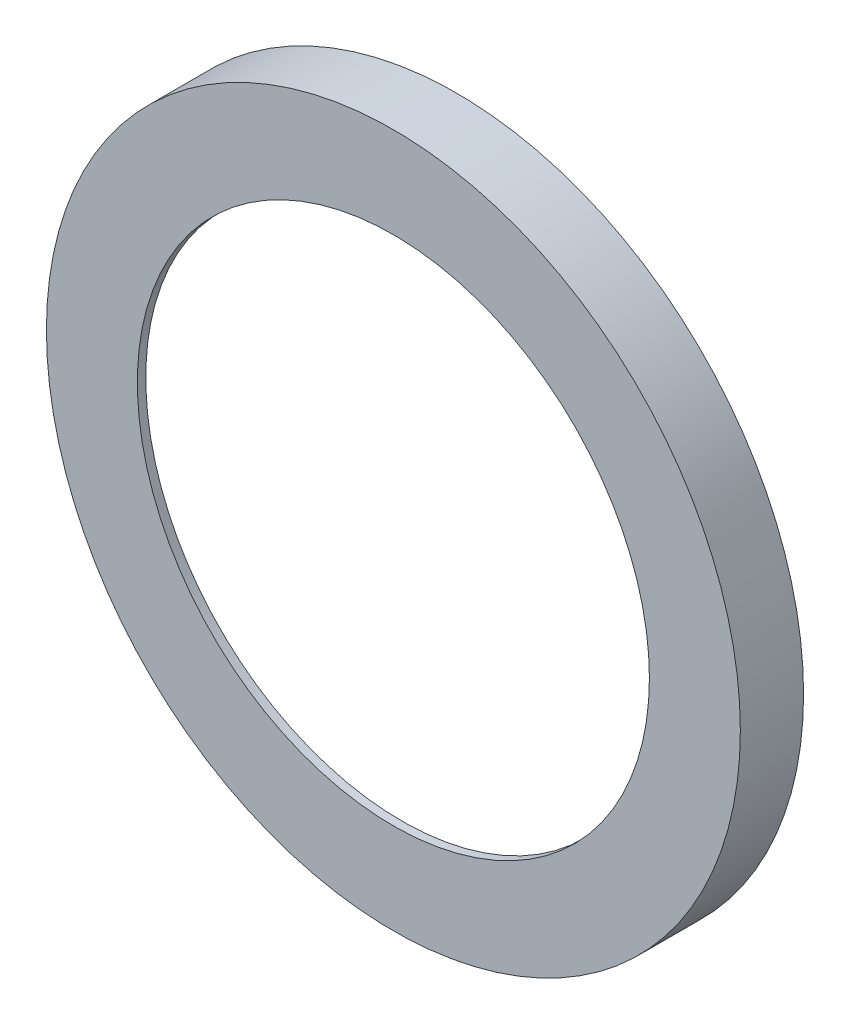
SolidWorks part; units mm, degrees
ref_plane "Front Plane" through (0, 0, 0) normal (0, 0, 1) x (1, 0, 0)
ref_plane "Top Plane" through (0, 0, 0) normal (0, 1, 0) x (1, 0, 0)
ref_plane "Right Plane" through (0, 0, 0) normal (1, 0, 0) x (0, 0, -1)
sketch "Sketch1" plane through (0, 0, 0) normal (0, 1, 0) x (1, 0, 0)
  line L0 (0, 0) -> (0, 55.9741) construction
  line L1 (-171.45, 14.7142) -> (171.45, 14.7142) construction
  line L2 (77.1221, 2.5222) -> (77.1221, 5.0622)
  line L3 (77.1221, 5.0622) -> (100.7008, 21.5722)
  line L4 (100.7008, 21.5722) -> (104.5108, 21.5722)
  line L5 (104.5108, 21.5722) -> (104.5108, 2.5222)
  line L6 (104.5108, 2.5222) -> (77.1221, 2.5222)
  line L8 (76.3601, 1.3792) -> (76.3601, -10.8375) construction
  dimension "D1" = 19.05
  dimension "D2" = 0.762
  dimension "D3" = 3.81
  dimension "D4" = 2.54
  dimension "D5" = 35
  dimension "D6" = 6.858
revolve "Revolve1" add sketch "Sketch1" angle 360 about L0
sketch "Sketch2" [suppressed] plane through (0, 0, -21.5722) normal (0, 0, -1) x (-1, 0, 0)
  line L0 (-93.984, 0) -> (-77.1221, 0) construction
  line L1 (-93.984, 1.7145) -> (-77.1221, 1.7145)
  line L2 (-93.984, -1.7145) -> (-77.1221, -1.7145)
  line L3 (0, 0) -> (-77.1221, 0) construction
  arc A0 (-93.984, 1.7145) -> (-93.984, -1.7145) centre (-93.984, 0) ccw
  arc A1 (-77.1221, -1.7145) -> (-77.1221, 1.7145) centre (-77.1221, 0) ccw
  circle A2 centre (0, 0) radius 77.1221 construction
  arc A3 (-93.984, 1.5875) -> (-93.984, -1.5875) centre (-93.984, 0) ccw construction
  point P2 (-85.553, 0)
  dimension "D1" = 3.429
extrude "Cut-Extrude1" [suppressed] cut sketch "Sketch2" against normal blind 16.51
sketch "Sketch3" plane through (0, 0, 0) normal (1, 0, 0) x (0, 0, -1)
  circle A0 centre (13.9522, 17.78) radius 2.54
  circle A2 centre (13.9522, -17.78) radius 2.54
  dimension "D1" = 5.08
extrude "Cut-Extrude2" [suppressed] cut sketch "Sketch3" against normal through all both and the other way through all
